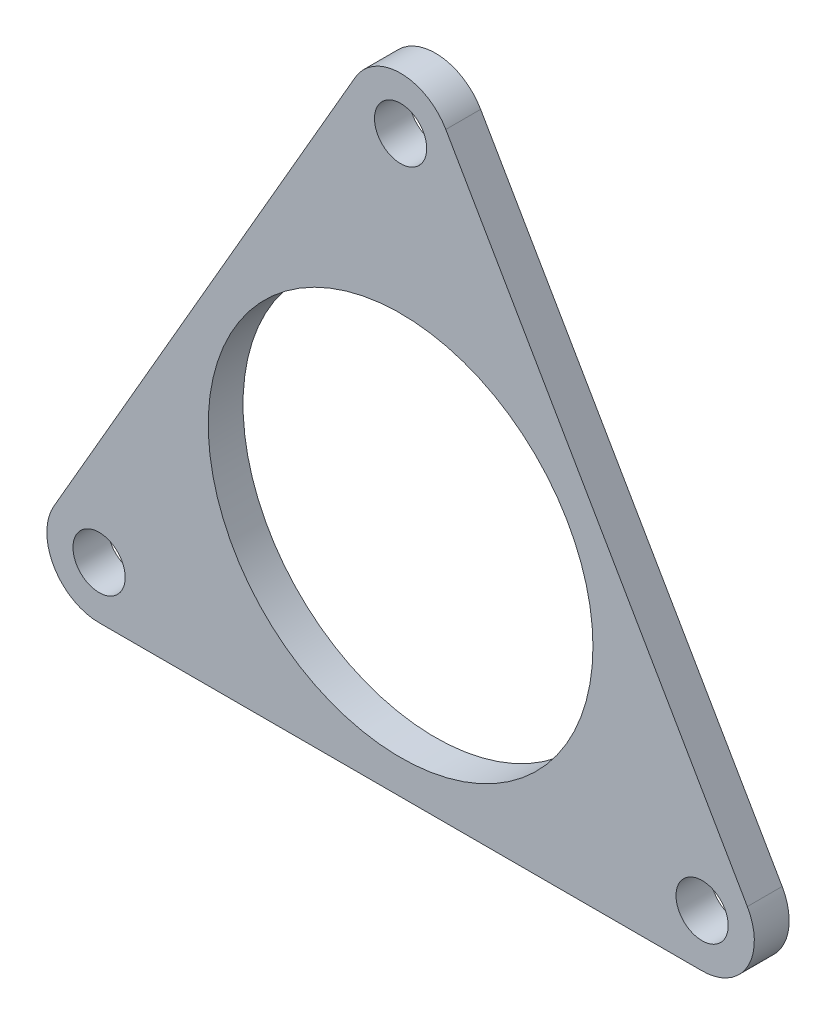
SolidWorks part; units mm, degrees
material "Thornel Mat VMA"
ref_plane "前视基准面" through (0, 0, 0) normal (0, 0, 1) x (1, 0, 0)
ref_plane "上视基准面" through (0, 0, 0) normal (0, 1, 0) x (1, 0, 0)
ref_plane "右视基准面" through (0, 0, 0) normal (1, 0, 0) x (0, 0, -1)
sketch "草图1" plane through (0, 0, 0) normal (0, 0, 1) x (1, 0, 0)
  line L0 (0, 20) -> (-17.3205, -10) construction
  line L1 (-17.3205, -10) -> (17.3205, -10) construction
  line L2 (17.3205, -10) -> (0, 20) construction
  line L3 (-2.5981, 21.5) -> (-19.9186, -8.5)
  line L4 (-17.3205, -13) -> (17.3205, -13)
  line L5 (19.9186, -8.5) -> (2.5981, 21.5)
  circle A0 centre (0, 0) radius 20 construction
  circle A1 centre (-17.3205, -10) radius 1.5
  circle A2 centre (0, 20) radius 1.5
  circle A3 centre (17.3205, -10) radius 1.5
  circle A4 centre (0, 0) radius 5 construction
  circle A5 centre (0, 0) radius 7 construction
  circle A6 centre (0, 7) radius 1.5 construction
  circle A7 centre (0, -7) radius 1.5 construction
  circle A8 centre (0, 0) radius 26 construction
  arc A9 (-19.9186, -8.5) -> (-17.3205, -13) centre (-17.3205, -10) ccw
  arc A10 (17.3205, -13) -> (19.9186, -8.5) centre (17.3205, -10) ccw
  arc A11 (-2.5981, 21.5) -> (2.5981, 21.5) centre (0, 20) cw
  circle A12 centre (0, 0) radius 11.05
  point P23 (-22.5167, -13)
  point P26 (22.5167, -13)
  point P29 (0, 26)
  dimension "D1" = 40
  dimension "D2" = 3
  dimension "D3" = 10
  dimension "D4" = 14
  dimension "D5" = 3
  dimension "D6" = 3
  dimension "D7" = 3
  dimension "D8" = 22.1
extrude "凸台-拉伸1" add sketch "草图1" along normal blind 2
